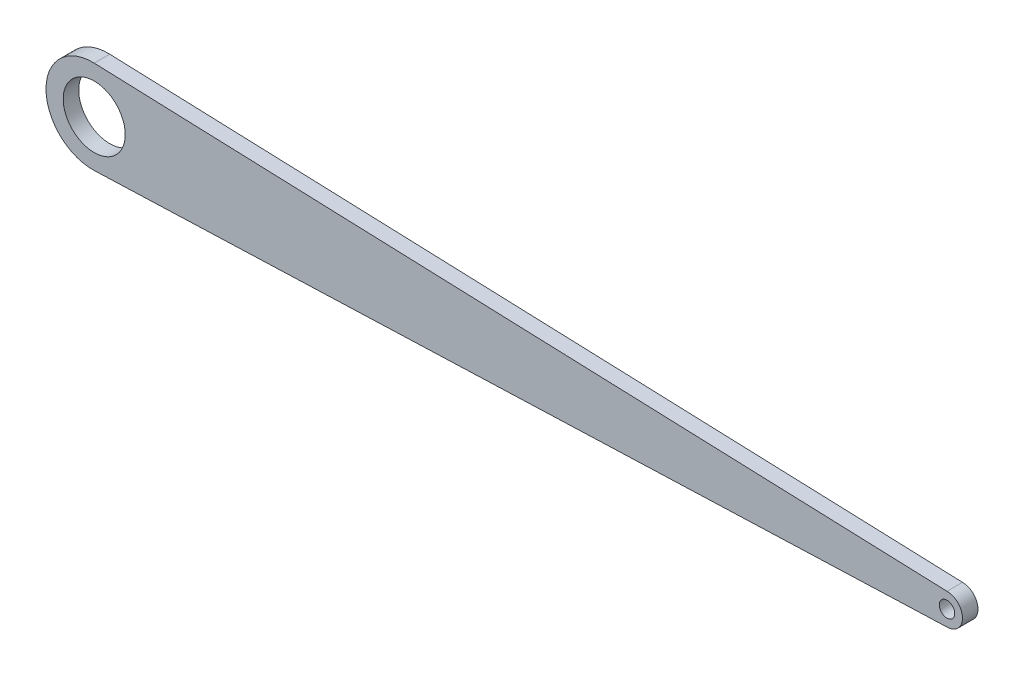
SolidWorks part; units mm, degrees
ref_plane "Plano frontal" through (0, 0, 0) normal (0, 0, 1) x (1, 0, 0)
ref_plane "Plano superior" through (0, 0, 0) normal (0, 1, 0) x (1, 0, 0)
ref_plane "Plano direito" through (0, 0, 0) normal (1, 0, 0) x (0, 0, -1)
sketch "Esboço1" plane through (0, 0, 0) normal (0, 0, 1) x (1, 0, 0)
  line L7 (-137.5, 0) -> (-137.5, -15) construction
  line L8 (-137.5, -15) -> (137.5, -5)
  line L9 (-137.5, 15) -> (137.5, 5)
  arc A6 (137.5, 5) -> (137.5, -5) centre (137.5, 0) cw
  circle A7 centre (-137.5, 0) radius 10
  circle A8 centre (137.5, 0) radius 2.5
  arc A9 (-137.5, 15) -> (-137.5, -15) centre (-138.0455, 0) ccw
  point P3 (0, 5)
extrude "Ressalto-extrusão1" add sketch "Esboço1" along normal blind 5
sketch "Esboço2" plane through (0, 0, 5) normal (0, 0, 1) x (1, 0, 0)
  point P0 (137.5, 0)
